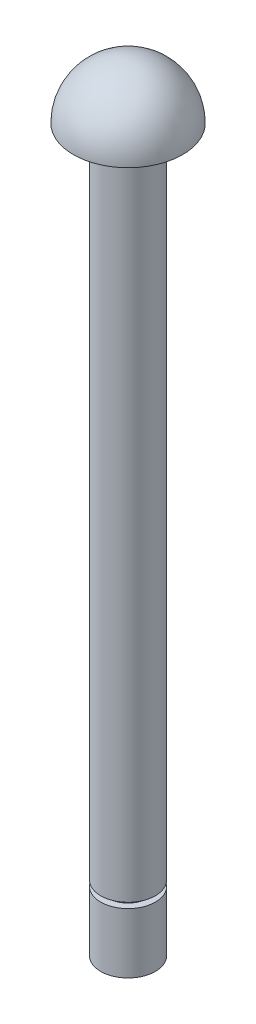
SolidWorks part; units mm, degrees
ref_plane "Front Plane" through (0, 0, 0) normal (0, 0, 1) x (1, 0, 0)
ref_plane "Top Plane" through (0, 0, 0) normal (0, 1, 0) x (1, 0, 0)
ref_plane "Right Plane" through (0, 0, 0) normal (1, 0, 0) x (0, 0, -1)
sketch "Sketch1" plane through (0, 0, 0) normal (0, 1, 0) x (1, 0, 0)
  circle A0 centre (0, 0) radius 2.5
extrude "Boss-Extrude1" add sketch "Sketch1" along normal blind 66
sketch "Sketch3" plane through (0, 0, 0) normal (1, 0, 0) x (0, 0, -1)
  line L0 (0, 66) -> (0, 71)
  line L3 (2.5, 66) -> (-2.5, 66) construction
  line L4 (0, 66) -> (5, 66)
  arc A1 (5, 66) -> (0, 71) centre (0, 66) ccw
revolve "Revolve1" add sketch "Sketch3" angle 360 about L0
ref_plane "Plane1" through (0, 66, 0) normal (-1, 0, 0) x (0, 0, -1)
ref_plane "Plane2" through (0, 66, 0) normal (-1, 0, 0) x (0, 0, -1)
sketch "Sketch8" plane through (0, 66, 0) normal (-1, 0, 0) x (0, 0, -1)
  line L0 (2.5, 60) -> (2.5, 60.5)
  line L1 (2.5, 0) -> (2.5, 66) construction
  line L2 (2.5, 60.5) -> (1.875, 60.5)
  line L3 (1.875, 60.5) -> (1.875, 60)
  line L4 (0, -50) -> (0, 50) construction
  line L5 (0, 0) -> (0, 60)
  line L6 (1.875, 60) -> (2.5, 60)
revolve "Cut-Revolve3" cut sketch "Sketch8" angle 360 about L5
